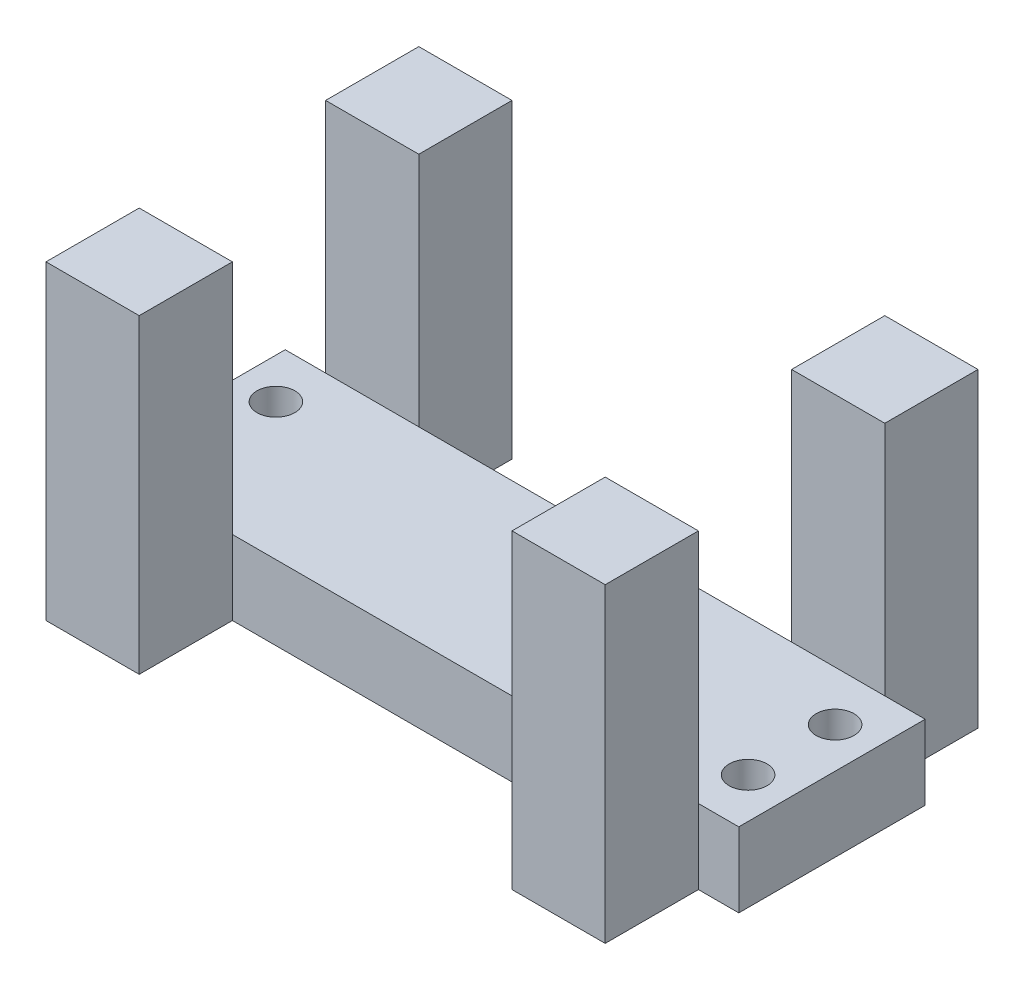
SolidWorks part; units mm, degrees
ref_plane "Front Plane" through (0, 0, 0) normal (0, 0, 1) x (1, 0, 0)
ref_plane "Top Plane" through (0, 0, 0) normal (0, 1, 0) x (1, 0, 0)
ref_plane "Right Plane" through (0, 0, 0) normal (1, 0, 0) x (0, 0, -1)
sketch "Sketch1" plane through (0, 0, 0) normal (0, 1, 0) x (1, 0, 0)
  line L1 (0, 0) -> (103, 0)
  line L2 (0, 0) -> (0, 30)
  line L3 (0, 30) -> (103, 30)
  line L4 (103, 0) -> (103, 30)
  dimension "D1" = 30
  dimension "D2" = 103
extrude "Boss-Extrude1" add sketch "Sketch1" along normal blind 12
sketch "Sketch2" plane through (0, 12, 0) normal (0, 1, 0) x (1, 0, 0)
  line L0 (0, 15) -> (103, 15) construction
  line L1 (0, 30) -> (0, 0) construction
  line L2 (103, 0) -> (103, 30) construction
  line L3 (51.5, 30) -> (51.5, 0) construction
  line L4 (103, 30) -> (0, 30) construction
  line L5 (0, 0) -> (103, 0) construction
  circle A0 centre (6.5, 8) radius 3.05
  circle A1 centre (6.5, 22) radius 3.05
  circle A2 centre (96.5, 8) radius 3.05
  circle A3 centre (96.5, 22) radius 3.05
  dimension "D1" = 6.1
  dimension "D3" = 8
  dimension "D2" = 6.5
extrude "Cut-Extrude1" cut sketch "Sketch2" against normal blind 12
sketch "Sketch4" plane through (0, 0, 0) normal (0, -1, 0) x (1, 0, 0)
  line L0 (0, 0) -> (103, 0) construction
  line L1 (96.5, 0) -> (81.5, 0)
  line L2 (96.5, 0) -> (96.5, 15)
  line L3 (96.5, 15) -> (81.5, 15)
  line L4 (81.5, 0) -> (81.5, 15)
  line L5 (103, -30) -> (0, -30) construction
  line L10 (96.5, -30) -> (81.5, -30)
  line L11 (96.5, -30) -> (96.5, -45)
  line L12 (96.5, -45) -> (81.5, -45)
  line L13 (81.5, -30) -> (81.5, -45)
  line L14 (51.5, -30) -> (51.5, 0) construction
  line L19 (21.5, -30) -> (21.5, -45)
  line L20 (6.5, -45) -> (21.5, -45)
  line L21 (6.5, -30) -> (6.5, -45)
  line L22 (6.5, -30) -> (21.5, -30)
  line L23 (6.5, 0) -> (6.5, 15)
  line L24 (21.5, 0) -> (21.5, 15)
  line L25 (6.5, 15) -> (21.5, 15)
  line L26 (6.5, 0) -> (21.5, 0)
  dimension "D1" = 15
  dimension "D2" = 30
  dimension "D3" = 30
  dimension "D4" = 15
  dimension "D5" = 15
  dimension "D8" = 15
extrude "Boss-Extrude3" add sketch "Sketch4" against normal blind 50
